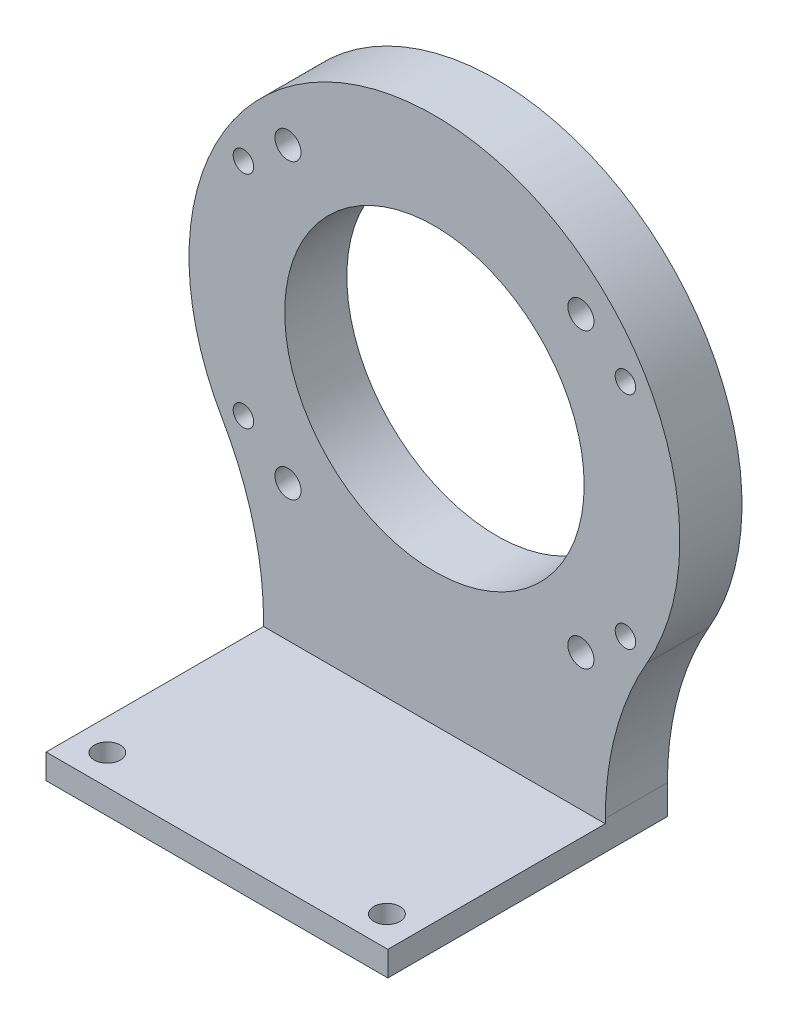
SolidWorks part; units mm, degrees
ref_plane "Front Plane" through (0, 0, 0) normal (0, 0, 1) x (1, 0, 0)
ref_plane "Top Plane" through (0, 0, 0) normal (0, 1, 0) x (1, 0, 0)
ref_plane "Right Plane" through (0, 0, 0) normal (1, 0, 0) x (0, 0, -1)
sketch "Sketch1" plane through (0, 0, 0) normal (0, 0, 1) x (1, 0, 0)
  line L0 (-27.5, -35.5) -> (27.5, -35.5) construction
  line L1 (0, -35.5) -> (0, -45.5) construction
  line L2 (-27.5, -28.3549) -> (-27.5, -45.5)
  line L3 (-27.5, -45.5) -> (27.5, -45.5)
  line L4 (27.5, -28.3549) -> (27.5, -45.5)
  circle A0 centre (0, 0) radius 24.1
  circle A1 centre (0, 0) radius 35.5 construction
  arc A2 (27.5, -28.3549) -> (-27.5, -28.3549) centre (0, 0) ccw
  point P10 (0, -35.5)
  point P12 (-17.75, -30.7439)
  point P13 (-30.7439, -17.75)
  point P14 (-35.5, 0)
  point P15 (-30.7439, 17.75)
  point P16 (-17.75, 30.7439)
  point P17 (0, 35.5)
  point P18 (17.75, 30.7439)
  point P19 (30.7439, 17.75)
  point P20 (35.5, 0)
  point P21 (30.7439, -17.75)
  point P22 (17.75, -30.7439)
  point P23 (0, 0)
  dimension "D1" = 48.2
  dimension "D2" = 71
  dimension "D4" = 79
  dimension "D5" = 55
  dimension "D6" = 10
  dimension "D3" = 12
extrude "Boss-Extrude1" add sketch "Sketch1" along normal blind 10
sketch "Sketch2" plane through (0, 0, 0) normal (0, 0, -1) x (-1, 0, 0)
  line L1 (23.5732, -23.5732) -> (-23.5732, -23.5732) construction
  line L2 (23.5732, -23.5732) -> (23.5732, 23.5732) construction
  line L3 (23.5732, 23.5732) -> (-23.5732, 23.5732) construction
  line L4 (-23.5732, -23.5732) -> (-23.5732, 23.5732) construction
  line L5 (23.5732, -23.5732) -> (-23.5732, 23.5732) construction
  line L6 (23.5732, 23.5732) -> (-23.5732, -23.5732) construction
  circle A0 centre (0, 0) radius 33.3375 construction
  point P8 (-23.5732, 23.5732)
  point P9 (23.5732, 23.5732)
  point P10 (23.5732, -23.5732)
  point P11 (-23.5732, -23.5732)
  dimension "D1" = 66.675
hole_wizard "Tap Drill for M5x0.8 Tap1" positions "3DSketch3" profile "Sketch6" hole size "M5x0.8" standard "ANSI Metric" end condition through all
sketch3d "3DSketch3"
  point P0 (23.5732, 23.5732, 0)
  point P3 (-23.5732, 23.5732, 0)
  point P6 (-23.5732, -23.5732, 0)
  point P9 (23.5732, -23.5732, 0)
sketch "Sketch6" plane through (23.5732, 23.5732, 0) normal (1, 0, 0) x (0, 1, 0)
  line L0 (0, 0) -> (0, 10)
  line L1 (0, 10) -> (2.1, 10)
  line L2 (2.1, 10) -> (2.1, 0)
  line L5 (2.1, 0) -> (0, 0)
  line L11 (0, -6.35) -> (0, 107.95) construction
  dimension "Thru Hole Dia." = 4.2
  dimension "Thru Hole Depth" = 10
sketch "Sketch7" plane through (0, 0, 10) normal (0, 0, 1) x (1, 0, 0)
  line L0 (-23.5732, 23.5732) -> (23.5732, -23.5732) construction
  circle A0 centre (0, 0) radius 35.5 construction
  point P4 (0, -35.5)
  point P8 (-17.75, -30.7439)
  point P9 (-30.7439, -17.75)
  point P10 (-35.5, 0)
  point P11 (-30.7439, 17.75)
  point P12 (-17.75, 30.7439)
  point P13 (0, 35.5)
  point P14 (17.75, 30.7439)
  point P15 (30.7439, 17.75)
  point P16 (35.5, 0)
  point P17 (30.7439, -17.75)
  point P18 (17.75, -30.7439)
  point P19 (0, 0)
  dimension "D1" = 71
  dimension "D2" = 12
hole_wizard "Tap Drill for M4x0.7 Tap1" positions "3DSketch4" profile "Sketch8" hole size "M4x0.7" standard "ANSI Metric" end condition through all
sketch3d "3DSketch4"
  point P0 (-30.7439, -17.75, 10)
  point P3 (-30.7439, 17.75, 10)
  point P6 (30.7439, 17.75, 10)
  point P9 (30.7439, -17.75, 10)
sketch "Sketch8" plane through (-30.7439, -17.75, 10) normal (1, 0, 0) x (0, -1, 0)
  line L0 (0, 0) -> (0, 10)
  line L1 (0, 10) -> (1.65, 10)
  line L2 (1.65, 10) -> (1.65, 0)
  line L5 (1.65, 0) -> (0, 0)
  line L11 (0, -6.35) -> (0, 107.95) construction
  dimension "Thru Hole Dia." = 3.3
  dimension "Thru Hole Depth" = 10
sketch "Sketch9" plane through (0, -45.5, 0) normal (0, -1, 0) x (1, 0, 0)
  line L0 (-27.5, 10) -> (-27.5, 0) construction
  line L1 (-27.5, 0) -> (27.5, 0)
  line L2 (-27.5, 0) -> (-27.5, 45)
  line L3 (-27.5, 45) -> (27.5, 45)
  line L4 (27.5, 0) -> (27.5, 45)
  line L5 (27.5, 10) -> (27.5, 0) construction
  line L6 (-27.5, 0) -> (27.5, 0) construction
  dimension "D1" = 45
extrude "Boss-Extrude2" add sketch "Sketch9" along normal blind 4
sketch "Sketch10" plane through (0, -49.5, 0) normal (0, -1, 0) x (1, 0, 0)
  line L1 (-22.5, 5.1527) -> (22.5, 5.1527) construction
  line L2 (-22.5, 5.1527) -> (-22.5, 40.1527) construction
  line L3 (-22.5, 40.1527) -> (22.5, 40.1527) construction
  line L4 (22.5, 5.1527) -> (22.5, 40.1527) construction
  line L5 (-22.5, 5.1527) -> (22.5, 40.1527) construction
  line L6 (-22.5, 40.1527) -> (22.5, 5.1527) construction
  point P0 (0, 22.6527)
  dimension "D1" = 35
  dimension "D2" = 45
hole_wizard "Tap Drill for M5x0.8 Tap2" positions "3DSketch6" profile "Sketch11" hole size "M5x0.8" standard "ANSI Metric"
sketch3d "3DSketch6"
  point P0 (-22.5, -49.5, 40.1527)
  point P3 (22.5, -49.5, 40.1527)
  point P6 (22.5, -49.5, 5.1527)
  point P9 (-22.5, -49.5, 5.1527)
sketch "Sketch11" plane through (-22.5, -49.5, 40.1527) normal (1, 0, 0) x (0, 0, -1)
  line L0 (0, 0) -> (0, 11.2618)
  line L1 (0, 11.2618) -> (2.1, 10)
  line L2 (2.1, 10) -> (2.1, 0)
  line L5 (2.1, 0) -> (0, 0)
  line L10 (0, 11.2618) -> (-2.1, 10) construction
  line L11 (0, -6.35) -> (0, 107.95) construction
  dimension "Hole Dia." = 4.2
  dimension "Hole Depth" = 10
  dimension "Drill Angle" = 118
fillet "Fillet1" radius 50 2 edges at (-27.5, -28.3549, 5) (27.5, -28.3549, 5)
